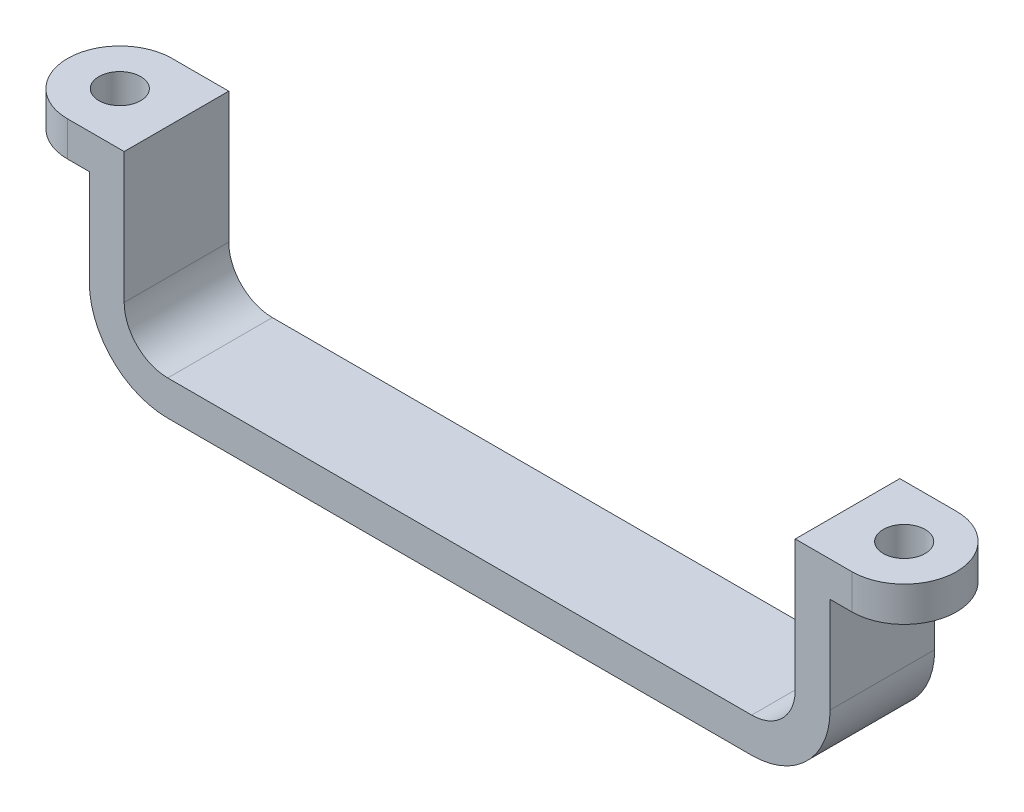
SolidWorks part; units mm, degrees
material "ABS"
ref_plane "Front Plane" through (0, 0, 0) normal (0, 0, 1) x (1, 0, 0)
ref_plane "Top Plane" through (0, 0, 0) normal (0, 1, 0) x (1, 0, 0)
ref_plane "Right Plane" through (0, 0, 0) normal (1, 0, 0) x (0, 0, -1)
sketch "Sketch1" plane through (0, 0, 0) normal (0, 0, 1) x (1, 0, 0)
  line L0 (-21.25, 10) -> (-21.25, 2.5)
  line L1 (-16.75, -2) -> (16.75, -2)
  line L2 (21.25, 10) -> (21.25, 2.5)
  line L4 (-19.25, 10) -> (-19.25, 2.5)
  line L5 (-16.75, 0) -> (16.75, 0)
  line L6 (19.25, 10) -> (19.25, 2.5)
  line L7 (-21.25, 10) -> (-19.25, 10)
  line L8 (19.25, 10) -> (21.25, 10)
  arc A0 (16.75, 0) -> (19.25, 2.5) centre (16.75, 2.5) ccw
  arc A1 (-19.25, 2.5) -> (-16.75, 0) centre (-16.75, 2.5) ccw
  arc A2 (-21.25, 2.5) -> (-16.75, -2) centre (-16.75, 2.5) ccw
  arc A3 (16.75, -2) -> (21.25, 2.5) centre (16.75, 2.5) ccw
  point P6 (0, 0)
  dimension "D3" = 38.5
  dimension "D2" = 10
  dimension "D1" = 2.5
  dimension "D5" = 10
  dimension "D4" = 2
extrude "Boss-Extrude1" add sketch "Sketch1" along normal blind 6
sketch "Sketch3" plane through (0, 10, 0) normal (0, 1, 0) x (-1, 0, 0)
  line L0 (-22.5, 3) -> (22.5, 3) construction
  line L1 (0, 6) -> (0, 0) construction
  line L2 (-16.75, 6) -> (-16.75, 0) construction
  line L3 (-21.25, 6) -> (-21.25, 0)
  line L5 (21.25, 6) -> (21.25, 0)
  line L6 (22.5, 0) -> (-22.5, 0)
  line L7 (-22.5, 6) -> (22.5, 6)
  circle A0 centre (-22.5, 3) radius 3
  circle A1 centre (-22.5, 3) radius 1.2
  circle A2 centre (22.5, 3) radius 1.2
  circle A3 centre (22.5, 3) radius 3
  point P1 (0, 3)
  point P13 (-16.75, 3)
  point P15 (0, 3)
  dimension "D2" = 2.4
  dimension "D3" = 6
extrude "Boss-Extrude6" add sketch "Sketch3" against normal blind 2
